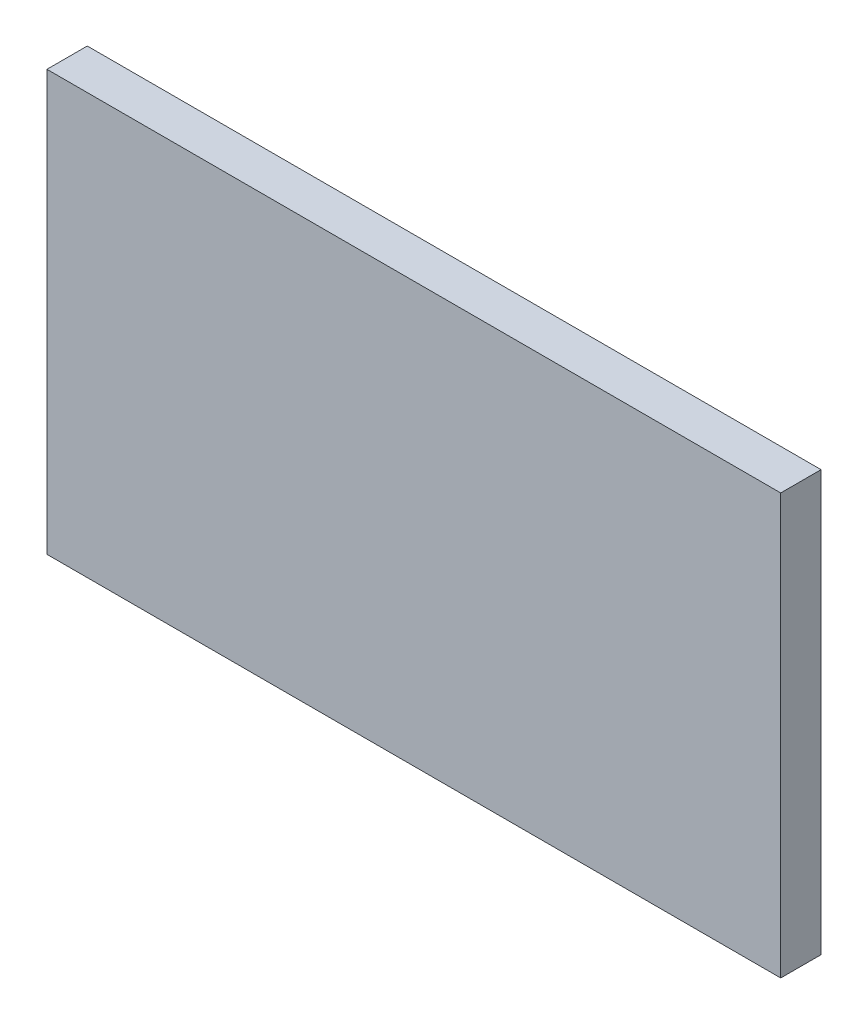
SolidWorks part; units mm, degrees
ref_plane "Front Plane" through (0, 0, 0) normal (0, 0, 1) x (1, 0, 0)
ref_plane "Top Plane" through (0, 0, 0) normal (0, 1, 0) x (1, 0, 0)
ref_plane "Right Plane" through (0, 0, 0) normal (1, 0, 0) x (0, 0, -1)
sketch "Sketch1" plane through (0, 0, 0) normal (0, 0, 1) x (1, 0, 0)
  line L1 (90.961, -52.0748) -> (-90.961, -52.0748)
  line L2 (90.961, -52.0748) -> (90.961, 52.0748)
  line L3 (90.961, 52.0748) -> (-90.961, 52.0748)
  line L4 (-90.961, -52.0748) -> (-90.961, 52.0748)
  line L5 (90.961, -52.0748) -> (-90.961, 52.0748) construction
  line L6 (90.961, 52.0748) -> (-90.961, -52.0748) construction
  point P0 (0, 0)
extrude "Boss-Extrude1" add sketch "Sketch1" along normal blind 10
